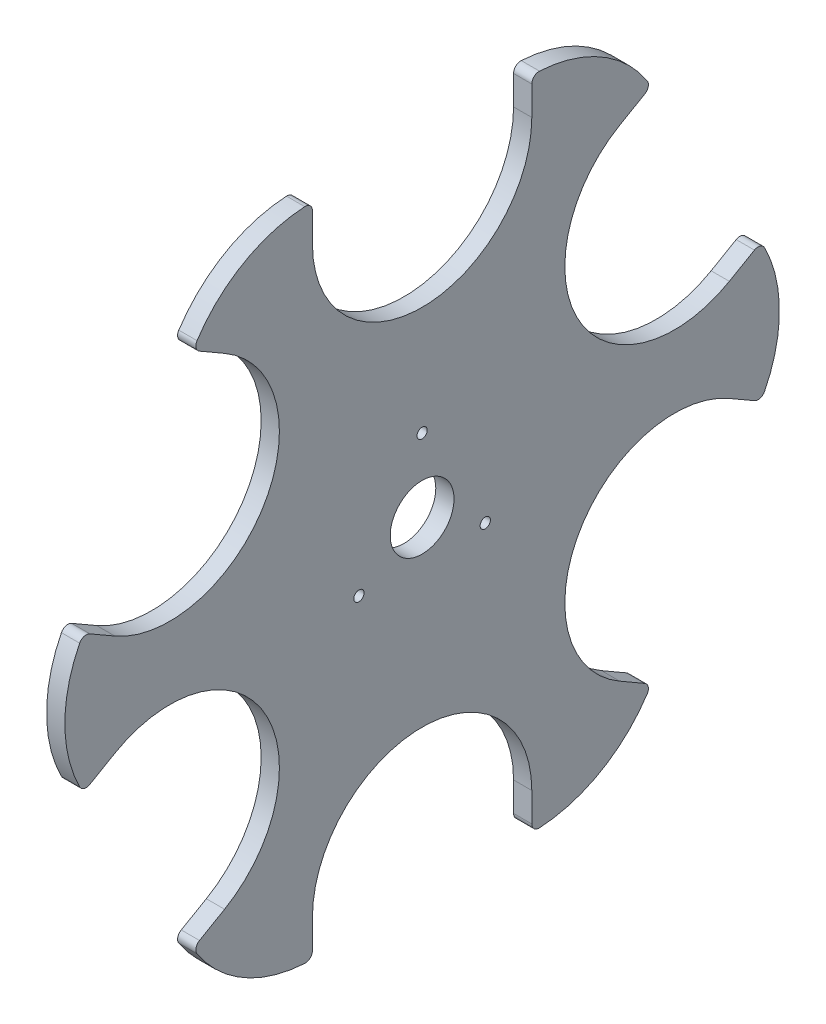
SolidWorks part; units mm, degrees
ref_plane "Front Plane" through (0, 0, 0) normal (0, 0, 1) x (1, 0, 0)
ref_plane "Top Plane" through (0, 0, 0) normal (0, 1, 0) x (1, 0, 0)
ref_plane "Right Plane" through (0, 0, 0) normal (1, 0, 0) x (0, 0, -1)
sketch "Sketch1" plane through (0, 0, 0) normal (1, 0, 0) x (0, 0, -1)
  line L0 (0, 0) -> (0, 101.5) construction
  line L1 (38.2, 101.5) -> (-38.2, 101.5) construction
  line L2 (107.0016, 17.6678) -> (68.8016, 83.8322) construction
  line L3 (0, 0) -> (87.9016, 50.75) construction
  line L4 (68.8016, -83.8322) -> (107.0016, -17.6678) construction
  line L5 (0, 0) -> (87.9016, -50.75) construction
  line L6 (-38.2, -101.5) -> (38.2, -101.5) construction
  line L7 (0, 0) -> (0, -101.5) construction
  line L8 (-107.0016, -17.6678) -> (-68.8016, -83.8322) construction
  line L9 (0, 0) -> (-87.9016, -50.75) construction
  line L10 (-68.8016, 83.8322) -> (-107.0016, 17.6678) construction
  line L11 (0, 0) -> (-87.9016, 50.75) construction
  line L17 (68.8016, 83.8322) -> (79.8001, 90.1822)
  line L18 (0, 0) -> (-53.5008, 92.6661) construction
  line L19 (-53.5008, 92.6661) -> (-70.5802, 122.2485) construction
  line L20 (-38.2, 66.1643) -> (-38.2, 114.2) construction
  line L21 (-38.2, 101.5) -> (-38.2, 114.2)
  line L22 (-68.8016, 83.8322) -> (-79.8001, 90.1822)
  line L24 (38.2, 101.5) -> (38.2, 114.2)
  line L25 (107.0016, -17.6678) -> (118.0001, -24.0178)
  line L26 (107.0016, 17.6678) -> (118.0001, 24.0178)
  line L27 (38.2, -101.5) -> (38.2, -114.2)
  line L28 (68.8016, -83.8322) -> (79.8001, -90.1822)
  line L29 (-68.8016, -83.8322) -> (-79.8001, -90.1822)
  line L30 (-38.2, -101.5) -> (-38.2, -114.2)
  line L31 (-107.0016, 17.6678) -> (-118.0001, 24.0178)
  line L32 (-107.0016, -17.6678) -> (-118.0001, -24.0178)
  arc A0 (-38.2, 101.5) -> (38.2, 101.5) centre (0, 101.5) ccw
  arc A1 (68.8016, 83.8322) -> (107.0016, 17.6678) centre (87.9016, 50.75) ccw
  arc A2 (107.0016, -17.6678) -> (68.8016, -83.8322) centre (87.9016, -50.75) ccw
  arc A3 (38.2, -101.5) -> (-38.2, -101.5) centre (0, -101.5) ccw
  arc A4 (-68.8016, -83.8322) -> (-107.0016, -17.6678) centre (-87.9016, -50.75) ccw
  arc A5 (-107.0016, 17.6678) -> (-68.8016, 83.8322) centre (-87.9016, 50.75) ccw
  circle A6 centre (0, 0) radius 11.1106
  arc A7 (-38.2, 114.2) -> (-79.8001, 90.1822) centre (-38.2, 66.1643) ccw
  arc A8 (79.8001, 90.1822) -> (38.2, 114.2) centre (38.2, 66.1643) ccw
  arc A9 (118.0001, -24.0178) -> (118.0001, 24.0178) centre (76.4, 0) ccw
  arc A10 (38.2, -114.2) -> (79.8001, -90.1822) centre (38.2, -66.1643) ccw
  arc A11 (-79.8001, -90.1822) -> (-38.2, -114.2) centre (-38.2, -66.1643) ccw
  arc A12 (-118.0001, 24.0178) -> (-118.0001, -24.0178) centre (-76.4, 0) ccw
  point P6 (0, 101.5)
  point P24 (0, 0)
  point P35 (0, 0)
  point P52 (0, 0)
  point P75 (0, 0)
  dimension "D6" = 22.2212
  dimension "D1" = 76.4
  dimension "D2" = 101.5
  dimension "D7" = 12.7
  dimension "D3" = 6
  dimension "D5" = 6
  dimension "D8" = 6
extrude "Boss-Extrude1" add sketch "Sketch1" along normal blind 6.35
hole_wizard "9/64 (0.14063) Diameter Hole1" positions "Sketch5" profile "Sketch4" hole size "9/64" standard "ANSI Inch" end condition through all
sketch "Sketch5" plane through (6.35, 0, 0) normal (1, 0, 0) x (0, 0, -1)
  point P0 (0, 25.4)
  dimension "D1" = 25.4
sketch "Sketch4" plane through (6.35, 25.4, 0) normal (0, 1, 0) x (0, 0, -1)
  line L0 (0, 0) -> (0, 6.35)
  line L1 (0, 6.35) -> (1.786, 6.35)
  line L2 (1.786, 6.35) -> (1.786, 0)
  line L5 (1.786, 0) -> (0, 0)
  line L11 (0, -6.35) -> (0, 107.95) construction
  dimension "Thru Hole Dia." = 3.572
  dimension "Thru Hole Depth" = 6.35
pattern_circular "CirPattern1" count 3 every 120 about axis through (0, 0, 0) along (1, 0, 0) of "9/64 (0.14063) Diameter Hole1"
fillet "Fillet1" radius 2.54 12 edges at (3.175, 90.1822, 79.8001) (3.175, 114.2, 38.2) (3.175, 114.2, -38.2) (3.175, 24.0178, 118.0001) (3.175, -90.1822, 79.8001) (3.175, -114.2, -38.2) (3.175, -24.0178, 118.0001) (3.175, -114.2, 38.2) (3.175, -90.1822, -79.8001) (3.175, -24.0178, -118.0001) (3.175, 24.0178, -118.0001) (3.175, 90.1822, -79.8001)
